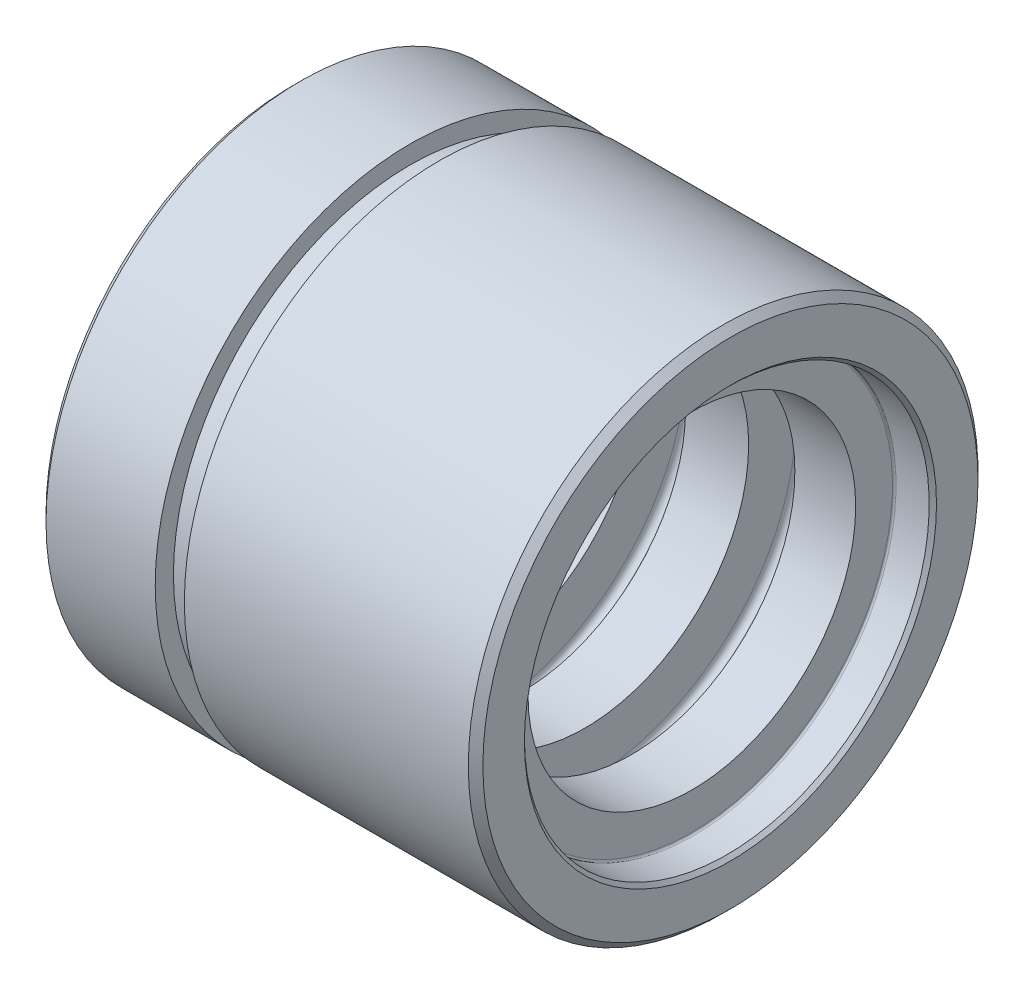
SolidWorks part; units mm, degrees
ref_plane "Front Plane" through (0, 0, 0) normal (0, 0, 1) x (1, 0, 0)
ref_plane "Top Plane" through (0, 0, 0) normal (0, 1, 0) x (1, 0, 0)
ref_plane "Right Plane" through (0, 0, 0) normal (1, 0, 0) x (0, 0, -1)
sketch "Sketch1" plane through (0, 0, 0) normal (0, 1, 0) x (1, 0, 0)
  line L0 (-2.2398, 0) -> (45.7246, 0) construction
  line L1 (0, -4.5342) -> (0, 37.3117) construction
  line L2 (0, 22.5) -> (25, 22.5)
  line L3 (25, 22.5) -> (25, 30)
  line L4 (25, 30) -> (31.35, 30)
  line L5 (31.35, 30) -> (31.35, 22.5)
  line L6 (31.35, 22.5) -> (40, 22.5)
  line L7 (40, 22.5) -> (40, 30)
  line L8 (40, 30) -> (46.35, 30)
  line L9 (46.35, 30) -> (46.35, 22.5)
  line L10 (46.35, 22.5) -> (54.7, 22.5)
  line L11 (54.7, 22.5) -> (54.7, 27.8)
  line L12 (54.7, 27.8) -> (60, 27.8)
  line L13 (60, 27.8) -> (60, 34)
  line L14 (59, 35) -> (20, 35)
  line L15 (20, 35) -> (20, 32.5)
  line L16 (20, 32.5) -> (16, 32.5)
  line L17 (16, 32.5) -> (16, 35)
  line L18 (16, 35) -> (1, 35)
  line L19 (0, 34) -> (0, 22.5)
  line L20 (1, 35) -> (0, 34)
  line L21 (60, 34) -> (59, 35)
  point P18 (60, 35)
  point P23 (0, 35)
  dimension "D1" = 22.5
  dimension "D2" = 25
  dimension "D3" = 6.35
  dimension "D4" = 8.65
  dimension "D5" = 6.35
  dimension "D6" = 5.3
  dimension "D7" = 5.3
  dimension "D8" = 7.5
  dimension "D9" = 4
  dimension "D10" = 2.5
  dimension "D11" = 16
  dimension "D12" = 12.5
  dimension "D13" = 60
revolve "Revolve1" add sketch "Sketch1" angle 360 about L0
fillet "Fillet1" radius 1 4 edges at (25, 0, 30) (31.35, 0, 30) (40, 0, 30) (46.35, 0, 30)
chamfer "Chamfer1" distance 0.5 angle 45 1 edges at (60, 0, 27.8)
fillet "Fillet2" radius 0.25 1 edges at (54.7, 0, 27.8)
